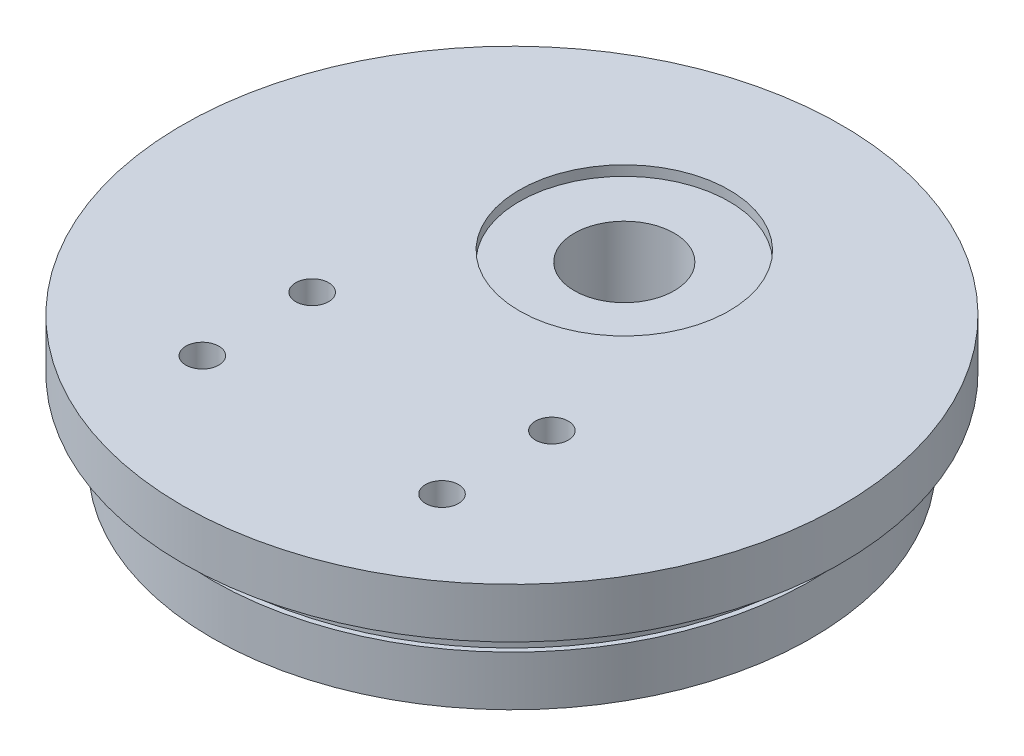
SolidWorks part; units mm, degrees
material "PC a densità alta"
ref_plane "Piano frontale" through (0, 0, 0) normal (0, 0, 1) x (1, 0, 0)
ref_plane "Piano superiore" through (0, 0, 0) normal (0, 1, 0) x (1, 0, 0)
ref_plane "Piano destro" through (0, 0, 0) normal (1, 0, 0) x (0, 0, -1)
sketch "Schizzo1" plane through (0, 0, 0) normal (0, 0, 1) x (1, 0, 0)
  line L0 (0, 0) -> (0, -38.3728) construction
  line L1 (0, 0) -> (-33, 0)
  line L2 (-33, 0) -> (-33, -5)
  line L3 (-33, -5) -> (-30, -5)
  line L4 (-30, -5) -> (-30, -13)
  line L5 (-30, -13) -> (0, -13)
  line L6 (0, -13) -> (0, 0)
  dimension "D1" = 5
  dimension "D2" = 8
  dimension "D3" = 66
  dimension "D4" = 60
revolve "Rivoluzione1" add sketch "Schizzo1" angle 360 about L0
sketch "Schizzo2" plane through (0, 0, 0) normal (0, 1, 0) x (1, 0, 0)
  circle A0 centre (0, 11.25) radius 5
  point P2 (0, 0)
  dimension "D1" = 10
  dimension "D2" = 11.25
extrude "Taglio-Estrusione1" cut sketch "Schizzo2" against normal through all
sketch "Schizzo3" plane through (0, -13, 0) normal (0, 1, 0) x (1, 0, 0)
  circle A0 centre (0, 11.25) radius 7
  dimension "D1" = 14
extrude "Taglio-Estrusione2" [suppressed] cut sketch "Schizzo3" along normal blind 8.1
hole_wizard "Preforo da maschiare M4-1" positions "Schizzo6" profile "Schizzo5" hole size "M4" standard "ISO"
sketch "Schizzo6" plane through (0, -13, 0) normal (0, -1, 0) x (1, 0, 0)
  point P0 (18.75, -14)
  point P15 (-18.75, -14)
  point P16 (18.75, 0)
  point P17 (-18.75, 0)
  point P18 (18.75, 14)
  point P19 (-18.75, 14)
  dimension "D1" = 18.75
  dimension "D2" = 14
  dimension "D3" = 2
  dimension "D4" = 3
sketch "Schizzo5" plane through (18.75, -13, -14) normal (1, 0, 0) x (0, 0, -1)
  line L0 (0, 0) -> (0, 5.9914)
  line L1 (0, 5.9914) -> (1.65, 5)
  line L2 (1.65, 5) -> (1.65, 0)
  line L5 (1.65, 0) -> (0, 0)
  line L10 (0, 5.9914) -> (-1.65, 5) construction
  line L11 (0, -6.35) -> (0, 107.95) construction
  dimension "Hole Dia." = 3.3
  dimension "Hole Depth" = 5
  dimension "Drill Angle" = 118
hole_wizard "Preforo da maschiare M4-2" positions "Schizzo8" profile "Schizzo7" hole size "M4" standard "ISO"
sketch "Schizzo8" plane through (-1.3169, 0, -6.3979) normal (0, 1, 0) x (-1, 0, 0)
  point P5 (-13.3169, 14.3979)
  point P7 (10.6831, 14.3979)
  point P10 (-13.3169, 25.3979)
  point P12 (10.6831, 25.3979)
  dimension "D1" = 12
  dimension "D4" = 11
  dimension "D5" = 8
  dimension "D6" = 12
sketch "Schizzo7" plane through (12, 0, 8) normal (1, 0, 0) x (0, 0, 1)
  line L0 (0, 0) -> (0, 6.9914)
  line L1 (0, 6.9914) -> (1.65, 6)
  line L2 (1.65, 6) -> (1.65, 0)
  line L5 (1.65, 0) -> (0, 0)
  line L10 (0, 6.9914) -> (-1.65, 6) construction
  line L11 (0, -6.35) -> (0, 107.95) construction
  dimension "Hole Dia." = 3.3
  dimension "Hole Depth" = 6
  dimension "Drill Angle" = 118
sketch "Schizzo9" plane through (0, 0, 0) normal (0, 0, 1) x (1, 0, 0)
  line L0 (0, 0) -> (0, -13) construction
  line L1 (-30, -5) -> (-29.5, -5)
  line L2 (-30, -5) -> (-30, -8)
  line L3 (-30, -8) -> (-29.5, -8)
  line L4 (-29.5, -5) -> (-29.5, -8)
  line L5 (33, 0) -> (-33, 0) construction
  line L6 (-30, -13) -> (30, -13) construction
  dimension "D1" = 3
  dimension "D2" = 0.5
revolve "Taglia-Rivoluzione1" cut sketch "Schizzo9" angle 360 about L0
sketch "Schizzo10" plane through (0, 0, 0) normal (0, 1, 0) x (1, 0, 0)
  circle A0 centre (0, 11.25) radius 10.5
  dimension "D1" = 21
extrude "Taglio-Estrusione3" cut sketch "Schizzo10" against normal blind 1
